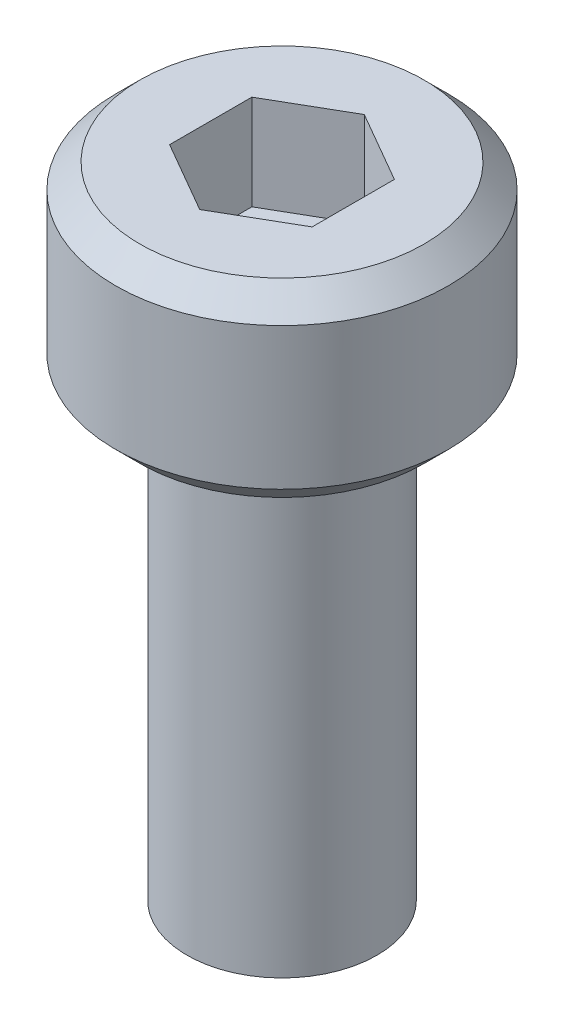
SolidWorks part; units mm, degrees
ref_plane "Front Plane" through (0, 0, 0) normal (0, 0, 1) x (1, 0, 0)
ref_plane "Top Plane" through (0, 0, 0) normal (0, 1, 0) x (1, 0, 0)
ref_plane "Right Plane" through (0, 0, 0) normal (1, 0, 0) x (0, 0, -1)
sketch "Sketch1" plane through (0, 0, 0) normal (0, 0, 1) x (1, 0, 0)
  line L0 (3.5, 4) -> (0, 4)
  line L1 (0, 4) -> (0, 0)
  line L2 (0, 0) -> (3.5, 0)
  line L3 (3.5, 0) -> (3.5, 4)
  line L4 (0, 4) -> (0, 0) construction
revolve "Revolve1" add sketch "Sketch1" angle 360 about L4
sketch "Sketch2" plane through (0, 0, 0) normal (0, -1, 0) x (1, 0, 0)
  circle A0 centre (0, 0) radius 2
extrude "Boss-Extrude1" add sketch "Sketch2" along normal blind 10
sketch "Sketch3" plane through (0, 4, 0) normal (0, 1, 0) x (-1, 0, 0)
  line L0 (-1.5, -0.866) -> (0, -1.7321)
  line L1 (0, -1.7321) -> (1.5, -0.866)
  line L2 (1.5, -0.866) -> (1.5, 0.866)
  line L3 (1.5, 0.866) -> (0, 1.7321)
  line L4 (0, 1.7321) -> (-1.5, 0.866)
  line L5 (-1.5, 0.866) -> (-1.5, -0.866)
extrude "Cut-Extrude1" cut sketch "Sketch3" against normal blind 2
chamfer "Chamfer1" distance 0.508 angle 45 2 edges at (3.5, 4, 0) (3.5, 0, 0)
chamfer "Chamfer2" distance 0.7696 angle 34.979 1 edges at (2, -10, 0)
